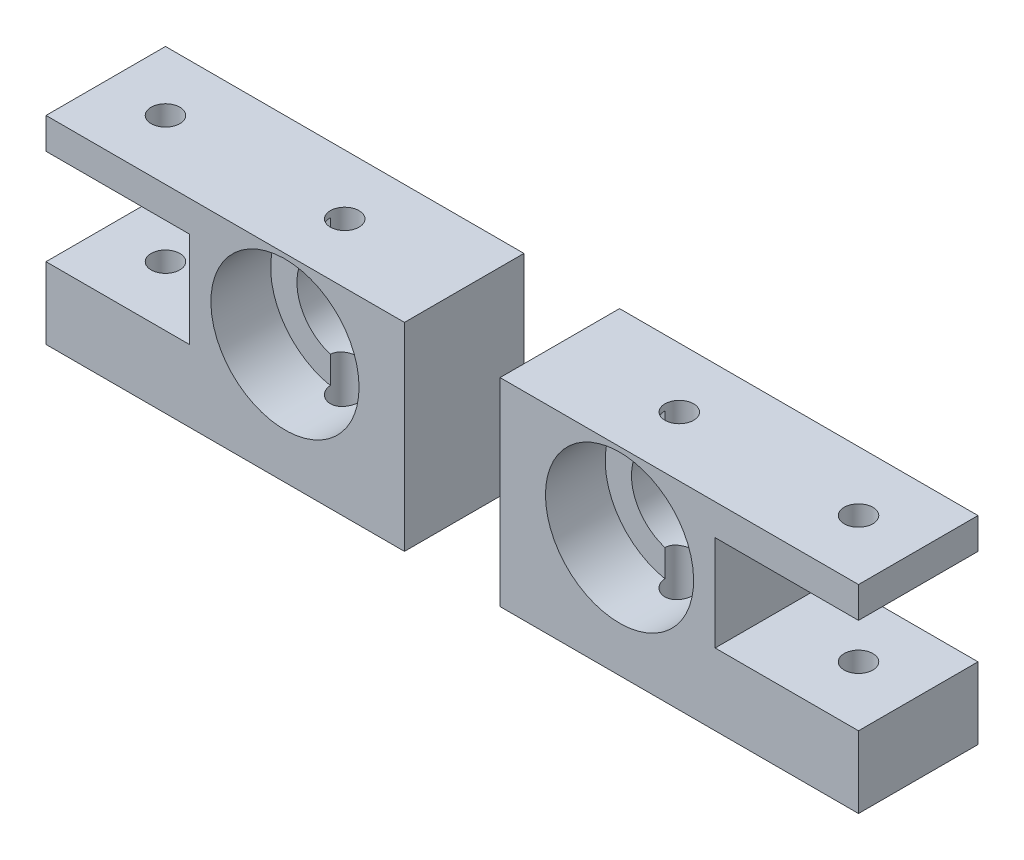
SolidWorks part; units mm, degrees
ref_plane "前视基准面" through (0, 0, 0) normal (0, 0, 1) x (1, 0, 0)
ref_plane "上视基准面" through (0, 0, 0) normal (0, 1, 0) x (1, 0, 0)
ref_plane "右视基准面" through (0, 0, 0) normal (1, 0, 0) x (0, 0, -1)
other "Configuration Table"
sketch "草图1" plane through (0, 0, 0) normal (0, 0, 1) x (1, 0, 0)
  line L1 (-10, -5) -> (10, -5)
  line L2 (-10, -5) -> (-10, 5)
  line L3 (-10, 5) -> (10, 5)
  line L4 (10, -5) -> (10, 5)
  line L5 (-10, -5) -> (10, 5) construction
  line L6 (-10, 5) -> (10, -5) construction
  circle A1 centre (0, 0) radius 3.1
  point P0 (0, 0)
  dimension "D1" = 10
  dimension "D3" = 6.2
  dimension "D2" = 20
extrude "凸台-拉伸1" add sketch "草图1" along normal blind 2.5 contours L1 L4 L3 L2 A1
sketch "草图2" plane through (0, 0, 0) normal (0, 0, -1) x (-1, 0, 0)
  line L0 (10, -5) -> (10, 5) construction
  line L1 (10, -5) -> (-10, -5)
  line L2 (10, -5) -> (10, 5)
  line L3 (10, 5) -> (-10, 5)
  line L4 (-10, -5) -> (-10, 5)
  line L5 (10, -5) -> (-10, -5) construction
  line L6 (10, 5) -> (-10, 5) construction
  line L12 (-10, -5) -> (-10, 5) construction
extrude "凸台-拉伸2" add sketch "草图2" along normal blind 2.5
sketch "草图3" plane through (0, -5, 0) normal (0, -1, 0) x (1, 0, 0)
  line L0 (0, -2.5) -> (0, 2.5) construction
  line L1 (10, -2.5) -> (-10, -2.5) construction
  line L2 (-10, 2.5) -> (10, 2.5) construction
  line L3 (10, 0) -> (-10, 0) construction
  line L4 (10, 2.5) -> (10, -2.5) construction
  line L5 (-10, 2.5) -> (-10, -2.5) construction
  circle A0 centre (-7.5, 0) radius 0.6
  circle A1 centre (0, 0) radius 0.6
  dimension "D1" = 1.2
  dimension "D2" = 2.5
extrude "切除-拉伸1" cut sketch "草图3" against normal through all contours A0 | A1
sketch "草图4" plane through (0, 0, -2.5) normal (0, 0, -1) x (-1, 0, 0)
  line L1 (10, -2) -> (4, -2)
  line L2 (10, -2) -> (10, 2)
  line L3 (10, 2) -> (4, 2)
  line L4 (4, -2) -> (4, 2)
  line L6 (10, 0) -> (4, 0) construction
  line L7 (10, -5) -> (10, 5) construction
  dimension "D1" = 4
  dimension "D2" = 6
extrude "切除-拉伸2" cut sketch "草图4" against normal through all
sketch "草图5" plane through (0, 0, 2.5) normal (0, 0, 1) x (1, 0, 0)
  circle A0 centre (0, 0) radius 2
  dimension "D1" = 4
extrude "切除-拉伸3" cut sketch "草图5" against normal through all
sketch "草图6" plane through (0, 0, 2.5) normal (0, 0, 1) x (1, 0, 0)
  line L0 (-10, 5) -> (10, 5) construction
  line L1 (10, 5) -> (-10, 5)
  line L2 (10, 5) -> (10, 3.3)
  line L3 (10, 3.3) -> (-10, 3.3)
  line L4 (-10, 5) -> (-10, 3.3)
  line L5 (-10, 2) -> (-10, 5) construction
  line L6 (10, -5) -> (10, 5) construction
  dimension "D1" = 1.7
extrude "切除-拉伸4" cut sketch "草图6" against normal through all
sketch "草图7" plane through (0, 0, 2.5) normal (0, 0, 1) x (1, 0, 0)
  line L0 (-10, -5) -> (10, -5) construction
  line L1 (10, 3.3) -> (5, 3.3)
  line L2 (10, 3.3) -> (10, -5)
  line L3 (10, -5) -> (5, -5)
  line L4 (5, 3.3) -> (5, -5)
  dimension "D1" = 5
extrude "切除-拉伸5" cut sketch "草图7" against normal through all
ref_plane "基准面1" through (7, 0, 0) normal (1, 0, 0) x (0, 0, -1)
mirror "镜向2" about plane through (7, 0, 0) normal (1, 0, 0) of bodies 216 214
